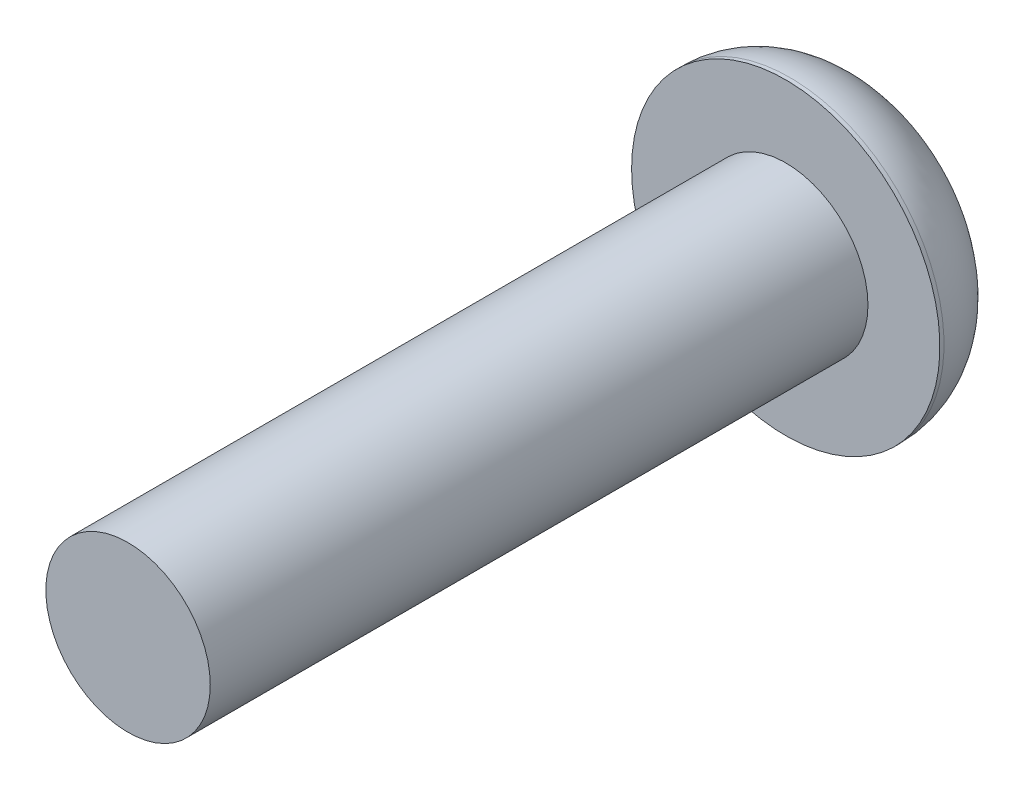
SolidWorks part; units mm, degrees
ref_plane "前视基准面" through (0, 0, 0) normal (0, 0, 1) x (1, 0, 0)
ref_plane "上视基准面" through (0, 0, 0) normal (0, 1, 0) x (1, 0, 0)
ref_plane "右视基准面" through (0, 0, 0) normal (1, 0, 0) x (0, 0, -1)
sketch "草图1" plane through (0, 0, 0) normal (0, 0, 1) x (1, 0, 0)
  circle A0 centre (0, 0) radius 2
extrude "凸台-拉伸1" add sketch "草图1" along normal blind 16
sketch "草图2" plane through (0, 0, 0) normal (0, 0, -1) x (-1, 0, 0)
  circle A0 centre (0, 0) radius 3.75
extrude "凸台-拉伸2" add sketch "草图2" along normal blind 2.1
fillet "圆角1" radius 2 1 edges at (-3.75, 0, -2.1)
